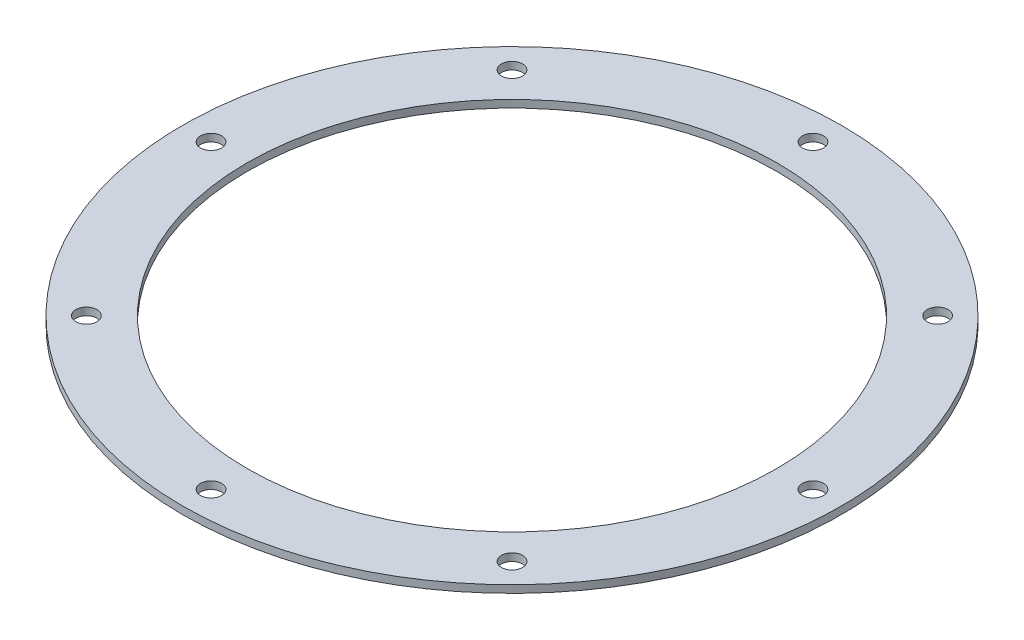
SolidWorks part; units mm, degrees
material "AISI 304"
ref_plane "Piano frontale" through (0, 0, 0) normal (0, 0, 1) x (1, 0, 0)
ref_plane "Piano superiore" through (0, 0, 0) normal (0, 1, 0) x (1, 0, 0)
ref_plane "Piano destro" through (0, 0, 0) normal (1, 0, 0) x (0, 0, -1)
sketch "Schizzo1" plane through (0, 0, 0) normal (0, 1, 0) x (1, 0, 0)
  circle A0 centre (0, 0) radius 176
  circle A1 centre (0, 0) radius 219
  circle A2 centre (0, 0) radius 200 construction
  circle A3 centre (0, 200) radius 7
  circle A4 centre (141.4214, 141.4214) radius 7
  circle A5 centre (200, 0) radius 7
  circle A6 centre (141.4214, -141.4214) radius 7
  circle A7 centre (0, -200) radius 7
  circle A8 centre (-141.4214, -141.4214) radius 7
  circle A9 centre (-200, 0) radius 7
  circle A10 centre (-141.4214, 141.4214) radius 7
  point P24 (0, 0)
  dimension "D1" = 8
extrude "Estrusione-Estrusione1" add sketch "Schizzo1" along normal mid plane 5
